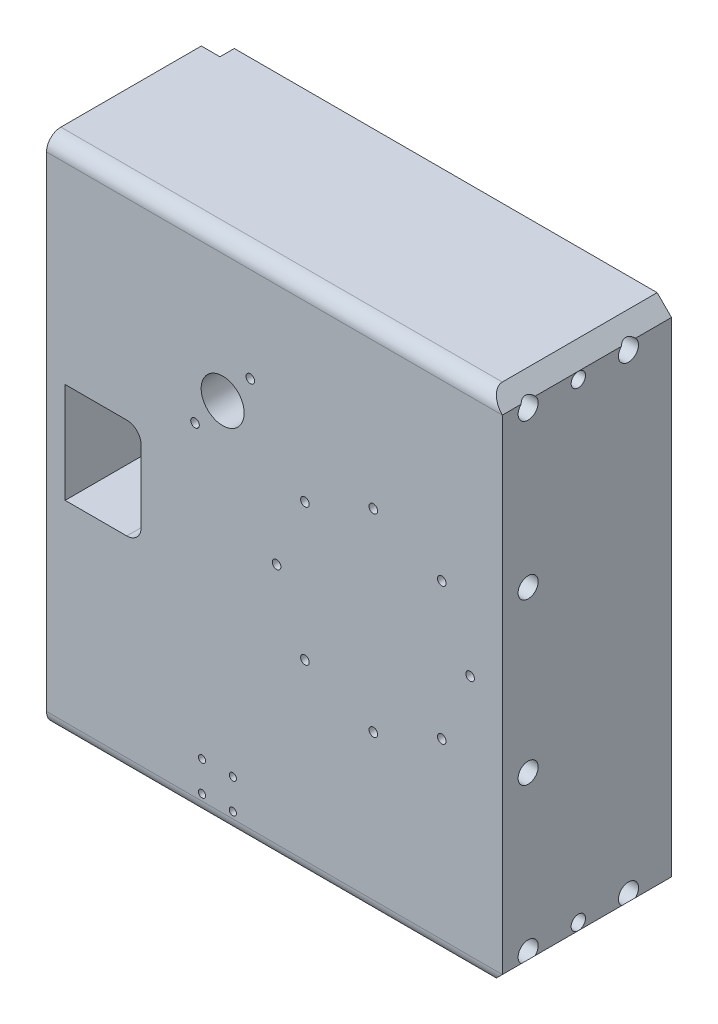
SolidWorks part; units mm, degrees
ref_plane "正面" through (0, 0, 0) normal (0, 0, 1) x (1, 0, 0)
ref_plane "平面" through (0, 0, 0) normal (0, 1, 0) x (1, 0, 0)
ref_plane "右側面" through (0, 0, 0) normal (1, 0, 0) x (0, 0, -1)
sketch "ｽｹｯﾁ1" plane through (0, 0, 0) normal (0, 0, 1) x (1, 0, 0)
  line L0 (0, 0) -> (308, 0)
  line L1 (308, 0) -> (318, 10)
  line L2 (318, 10) -> (318, 348)
  line L3 (318, 348) -> (308, 358)
  line L4 (308, 358) -> (0, 358)
  line L5 (0, 358) -> (0, 0)
extrude "ﾎﾞｽ - 押し出し1" add sketch "ｽｹｯﾁ1" along normal blind 118
sketch "ｽｹｯﾁ2" plane through (0, 0, 0) normal (0, 0, 1) x (1, 0, 0)
  line L0 (0, 0) -> (13, 0)
  line L1 (13, 0) -> (13, 358)
  line L2 (13, 358) -> (0, 358)
  line L3 (0, 358) -> (0, 0)
sketch "ｽｹｯﾁ3" plane through (0, 0, 0) normal (0, 0, 1) x (1, 0, 0)
  line L0 (0, 0) -> (13, 0)
  line L1 (13, 0) -> (13, 358)
  line L2 (13, 358) -> (0, 358)
  line L3 (0, 358) -> (0, 0)
extrude "ｶｯﾄ - 押し出し2" cut sketch "ｽｹｯﾁ3" along normal blind 10
fillet "ﾌｨﾚｯﾄ1" radius 10 2 edges at (154, 0, 118) (154, 358, 118)
sketch "ｽｹｯﾁ4" plane through (0, 0, 0) normal (0, 0, 1) x (1, 0, 0)
  circle A0 centre (228, 179) radius 62
sketch "ｽｹｯﾁ5" plane through (0, 0, 0) normal (0, 0, 1) x (1, 0, 0)
  circle A0 centre (228, 179) radius 62
extrude "ｶｯﾄ - 押し出し4" cut sketch "ｽｹｯﾁ5" along normal blind 10
ref_plane "平面1" through (0, 0, 10) normal (0, 0, 1) x (1, 0, 0)
sketch "ｽｹｯﾁ7" plane through (0, 0, 10) normal (0, 0, 1) x (1, 0, 0)
  circle A0 centre (228, 179) radius 74.5
ref_plane "平面2" through (0, 0, 10) normal (0, 0, 1) x (1, 0, 0)
sketch "ｽｹｯﾁ9" plane through (0, 0, 10) normal (0, 0, 1) x (1, 0, 0)
  circle A0 centre (228, 179) radius 74.5
sketch "ｽｹｯﾁ10" plane through (0, 0, 10) normal (0, 0, 1) x (1, 0, 0)
  circle A0 centre (228, 179) radius 74.5
extrude "ｶｯﾄ - 押し出し7" cut sketch "ｽｹｯﾁ10" along normal blind 6
sketch "ｽｹｯﾁ11" plane through (0, 0, 0) normal (0, 0, 1) x (1, 0, 0)
  circle A0 centre (295.5, 179) radius 3
  circle A1 centre (275.7297, 226.7297) radius 3
  circle A2 centre (228, 246.5) radius 3
  circle A3 centre (180.2703, 226.7297) radius 3
  circle A4 centre (160.5, 179) radius 3
  circle A5 centre (180.2703, 131.2703) radius 3
  circle A6 centre (228, 111.5) radius 3
  circle A7 centre (275.7297, 131.2703) radius 3
extrude "ｶｯﾄ - 押し出し8" cut sketch "ｽｹｯﾁ11" against normal through all and the other way through all
sketch "ｽｹｯﾁ12" plane through (0, 0, 0) normal (0, 0, 1) x (1, 0, 0)
  circle A0 centre (142.17, 282.07) radius 3
  circle A1 centre (103.6, 236.11) radius 3
extrude "ｶｯﾄ - 押し出し9" cut sketch "ｽｹｯﾁ12" against normal through all and the other way through all
sketch "ｽｹｯﾁ13" plane through (0, 0, 0) normal (0, 0, 1) x (1, 0, 0)
  circle A0 centre (108.5, 14.5) radius 2.5
  circle A1 centre (108.5, 35.5) radius 2.5
  circle A2 centre (130, 14.5) radius 2.5
  circle A3 centre (130, 35.5) radius 2.5
extrude "ｶｯﾄ - 押し出し10" cut sketch "ｽｹｯﾁ13" against normal through all and the other way through all
sketch "ｽｹｯﾁ14" plane through (0, 0, 0) normal (0, 0, 1) x (1, 0, 0)
  circle A0 centre (122.89, 259.09) radius 15
extrude "ｶｯﾄ - 押し出し11" cut sketch "ｽｹｯﾁ14" against normal through all and the other way through all
sketch "ｽｹｯﾁ15" plane through (0, 0, 0) normal (0, 0, 1) x (1, 0, 0)
  line L0 (13, 144) -> (56, 144)
  line L1 (66, 154) -> (66, 204)
  line L2 (56, 214) -> (13, 214)
  line L3 (13, 214) -> (13, 144)
  arc A0 (56, 144) -> (66, 154) centre (56, 154) ccw
  arc A1 (66, 204) -> (56, 214) centre (56, 204) ccw
extrude "ｶｯﾄ - 押し出し12" cut sketch "ｽｹｯﾁ15" against normal through all and the other way through all
sketch "ｽｹｯﾁ16" plane through (0, 0, 0) normal (1, 0, 0) x (0, 0, -1)
  circle A0 centre (0, 15) radius 7
  circle A1 centre (0, 343) radius 7
  circle A2 centre (0, 15) radius 7
  circle A3 centre (0, 123) radius 7
  circle A4 centre (0, 235) radius 7
  circle A5 centre (0, 343) radius 7
sketch "ｽｹｯﾁ17" plane through (0, 0, 0) normal (1, 0, 0) x (0, 0, -1)
  circle A0 centre (-30, 15) radius 7
  circle A1 centre (-30, 343) radius 7
  circle A2 centre (-100, 15) radius 7
  circle A3 centre (-100, 123) radius 7
  circle A4 centre (-100, 235) radius 7
  circle A5 centre (-100, 343) radius 7
extrude "ｶｯﾄ - 押し出し14" cut sketch "ｽｹｯﾁ17" against normal through all and the other way through all
sketch "ｽｹｯﾁ18" plane through (0, 0, 0) normal (1, 0, 0) x (0, 0, -1)
  circle A0 centre (-65, 15) radius 5
  circle A1 centre (-65, 343) radius 5
extrude "ｶｯﾄ - 押し出し15" cut sketch "ｽｹｯﾁ18" against normal through all and the other way through all
